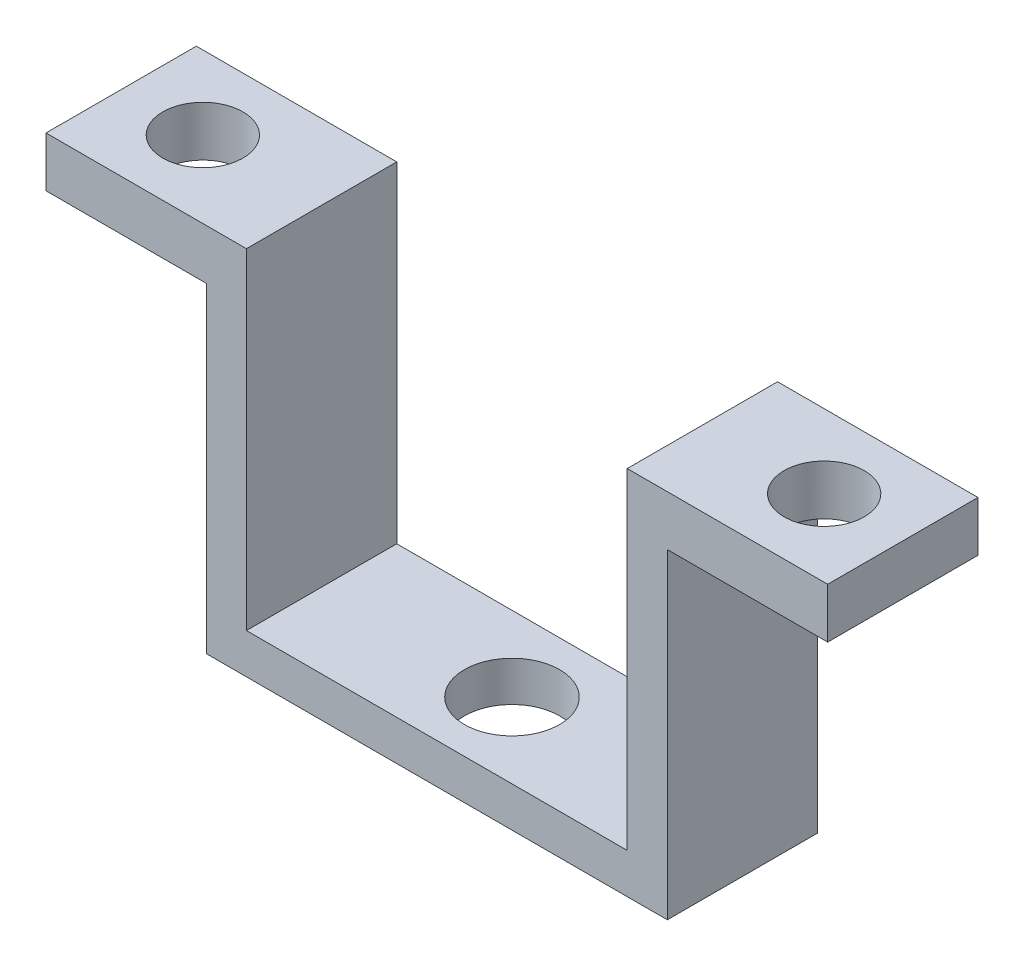
SolidWorks part; units mm, degrees
material "AISI 304"
ref_plane "Plano frontal" through (0, 0, 0) normal (0, 0, 1) x (1, 0, 0)
ref_plane "Plano superior" through (0, 0, 0) normal (0, 1, 0) x (1, 0, 0)
ref_plane "Plano direito" through (0, 0, 0) normal (1, 0, 0) x (0, 0, -1)
sketch "Esboço1" plane through (0, 0, 0) normal (0, 0, 1) x (1, 0, 0)
  line L0 (0, -61.9809) -> (0, 61.9809) construction
  line L1 (19, 0) -> (-19, 0)
  line L2 (-19, 0) -> (-19, 33)
  line L3 (-19, 33) -> (-39, 33)
  line L4 (-39, 33) -> (-39, 28)
  line L5 (-39, 28) -> (-23, 28)
  line L6 (-23, 28) -> (-23, -4)
  line L7 (-23, -4) -> (23, -4)
  line L9 (23, 28) -> (23, -4)
  line L10 (39, 28) -> (23, 28)
  line L11 (39, 33) -> (39, 28)
  line L12 (19, 33) -> (39, 33)
  line L13 (19, 0) -> (19, 33)
  point P4 (0, 0)
  point P7 (-29, 33)
  dimension "D1" = 19
  dimension "D2" = 23
  dimension "D3" = 20
  dimension "D4" = 5
  dimension "D5" = 4
  dimension "D6" = 33
extrude "Ressalto-extrusão1" add sketch "Esboço1" along normal mid plane 15
sketch "Esboço3" plane through (0, -4, 0) normal (0, -1, 0) x (-1, 0, 0)
  circle A0 centre (0, 0) radius 4.75
  dimension "D1" = 9.5
extrude "Corte-extrusão2" cut sketch "Esboço3" against normal through all both and the other way through all
sketch "Esboço4" plane through (0, 28, 0) normal (0, -1, 0) x (-1, 0, 0)
  line L1 (23, -7.5) -> (23, 7.5) construction
  line L2 (-23, -7.5) -> (-23, 7.5) construction
  circle A0 centre (31, 0.1493) radius 4
  circle A1 centre (-31, 0.1493) radius 4
  dimension "D1" = 8
  dimension "D2" = 8
extrude "Corte-extrusão3" cut sketch "Esboço4" against normal through all both and the other way through all
